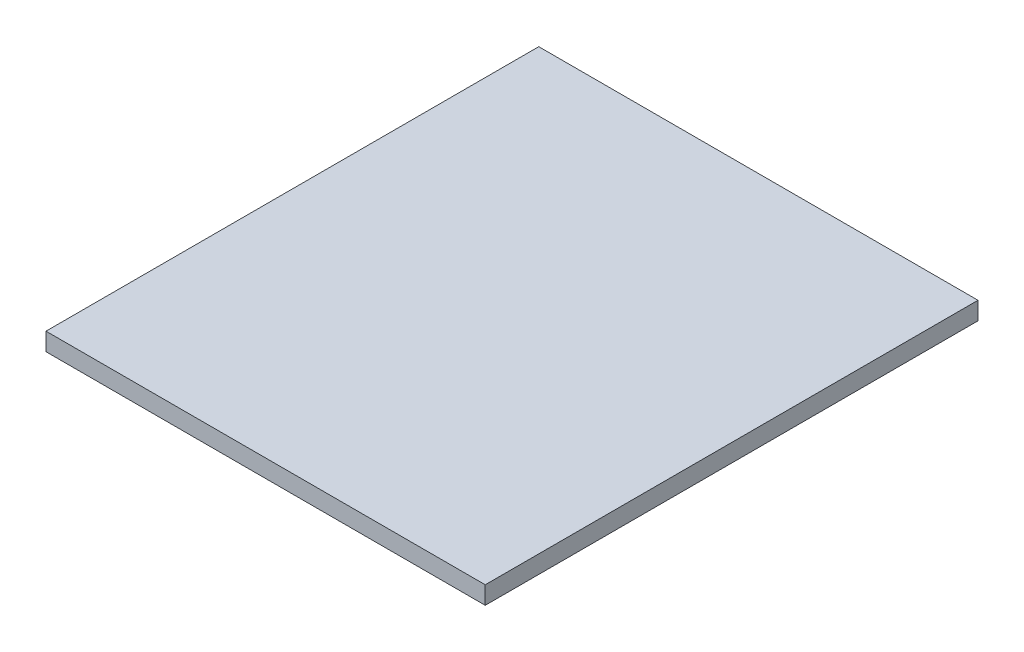
SolidWorks part; units mm, degrees
ref_plane "Alzado" through (0, 0, 0) normal (0, 0, 1) x (1, 0, 0)
ref_plane "Planta" through (0, 0, 0) normal (0, 1, 0) x (1, 0, 0)
ref_plane "Vista lateral" through (0, 0, 0) normal (1, 0, 0) x (0, 0, -1)
sketch "Croquis1" plane through (0, 0, 0) normal (0, 1, 0) x (1, 0, 0)
  line L1 (0, 0) -> (1252.4, 0)
  line L2 (0, 0) -> (0, -1405)
  line L3 (0, -1405) -> (1252.4, -1405)
  line L4 (1252.4, 0) -> (1252.4, -1405)
  dimension "D1" = 1252.4
  dimension "D2" = 1405
extrude "Saliente-Extruir1" add sketch "Croquis1" along normal blind 50.8
